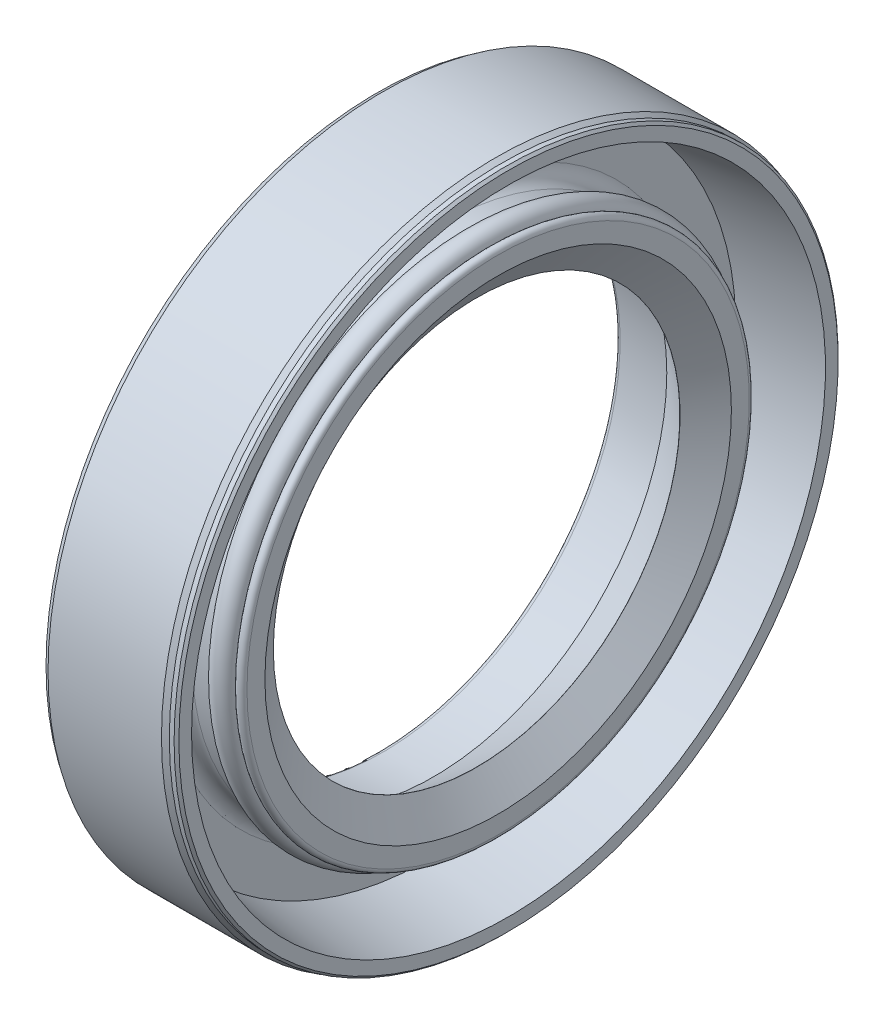
SolidWorks part; units mm, degrees
material "O-Ring (NBR)"
ref_plane "Front Plane" through (0, 0, 0) normal (0, 0, 1) x (1, 0, 0)
ref_plane "Top Plane" through (0, 0, 0) normal (0, 1, 0) x (1, 0, 0)
ref_plane "Right Plane" through (0, 0, 0) normal (1, 0, 0) x (0, 0, -1)
sketch "Sketch1" plane through (0, 0, 0) normal (0, 0, 1) x (1, 0, 0)
  line L0 (0.9025, 10.5) -> (0.9025, 9.75)
  line L1 (0.005, 8.5) -> (0.9025, 9.75)
  line L2 (0, 8.5) -> (0.005, 8.5)
  line L3 (-1.7975, 9.75) -> (0, 8.5)
  line L4 (-3.936, 9.9371) -> (-1.7975, 9.75)
  line L6 (-1.9975, 12.8333) -> (-1.9975, 11.1)
  line L7 (-1.3975, 10.5) -> (-0.4975, 10.5)
  line L8 (-4.1642, 13.8333) -> (-3.9142, 14)
  line L9 (-3.9142, 14) -> (0.828, 14)
  line L10 (0.828, 14) -> (1.0358, 13.88)
  line L11 (1.0358, 13.88) -> (1.2358, 13.88)
  line L12 (1.2358, 13.88) -> (1.3358, 13.78)
  line L13 (1.3358, 13.78) -> (1.3358, 13.25)
  line L14 (-1.9975, 12.8333) -> (1.3358, 13.25)
  line L23 (0, 0) -> (3.4778, 0) construction
  line L24 (0, 0) -> (0, 9.5021) construction
  line L25 (-4.1642, 13.8333) -> (-4.1642, 10.1861)
  arc A0 (0.9025, 10.5) -> (0.5025, 10.5) centre (0.7025, 10.5) ccw
  arc A1 (-4.1642, 10.1861) -> (-3.936, 9.9371) centre (-3.9142, 10.1861) ccw
  arc A2 (-1.9975, 11.1) -> (-1.3975, 10.5) centre (-1.3975, 11.1) ccw
  arc A3 (0.5025, 10.5) -> (-0.4975, 10.5) centre (0.0025, 10.5) ccw
  point P0 (0, 8.5)
  dimension "D2" = 0.5
  dimension "D1" = 8.5
  dimension "D4" = 0.25
  dimension "D5" = 28
  dimension "D3" = 5.5
  dimension "D6" = 0.12
  dimension "D7" = 30
  dimension "D8" = 0.3
  dimension "D9" = 45
  dimension "D10" = 0.1
  dimension "D11" = 17
revolve "Revolve2" add sketch "Sketch1" angle 360 about L23
